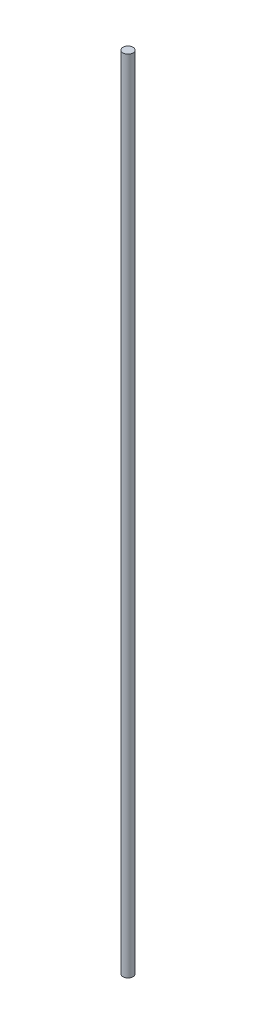
SolidWorks part; units mm, degrees
ref_plane "前视基准面" through (0, 0, 0) normal (0, 0, 1) x (1, 0, 0)
ref_plane "上视基准面" through (0, 0, 0) normal (0, 1, 0) x (1, 0, 0)
ref_plane "右视基准面" through (0, 0, 0) normal (1, 0, 0) x (0, 0, -1)
sketch "草图1" plane through (0, 0, 0) normal (0, 1, 0) x (1, 0, 0)
  circle A0 centre (0, 0) radius 2.5
  dimension "D1" = 5
extrude "凸台-拉伸1" add sketch "草图1" along normal blind 400
